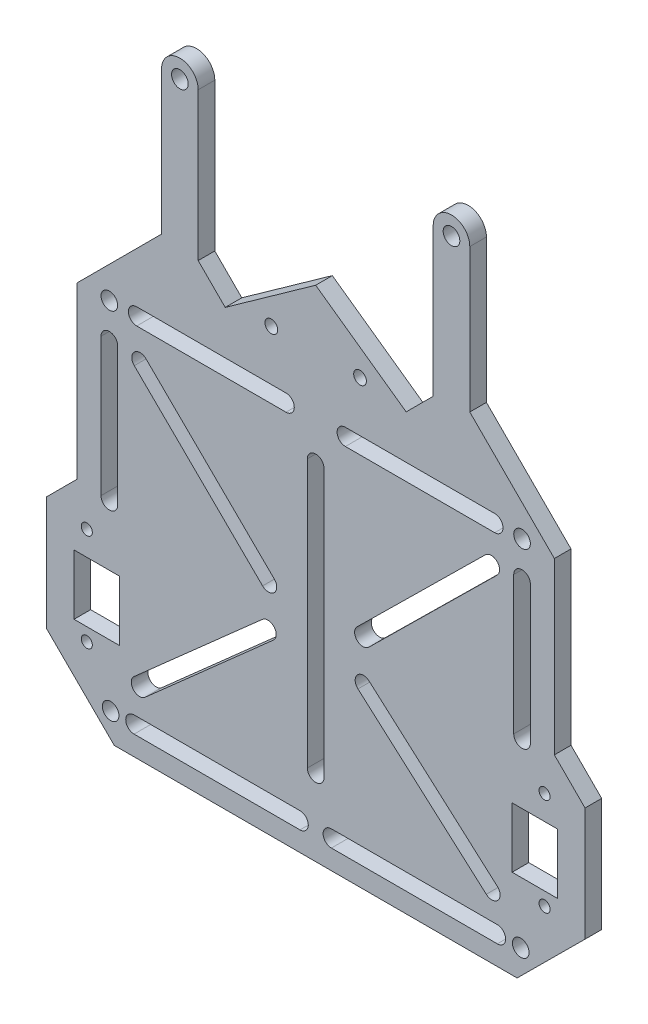
SolidWorks part; units mm, degrees
ref_plane "前视基准面" through (0, 0, 0) normal (0, 0, 1) x (1, 0, 0)
ref_plane "上视基准面" through (0, 0, 0) normal (0, 1, 0) x (1, 0, 0)
ref_plane "右视基准面" through (0, 0, 0) normal (1, 0, 0) x (0, 0, -1)
other "Configuration Table"
sketch "Model" plane through (0, 0, 0) normal (0, 0, 1) x (1, 0, 0)
  line L0 (-43.0594, 38.2199) -> (-48.5923, 32.687)
  line L1 (-43.0594, 68.8966) -> (-43.0594, 38.2199)
  line L2 (-27.8, 84.1561) -> (-43.0594, 68.8966)
  line L5 (-36.3443, 0) -> (36.3443, 0)
  line L12 (48.5923, 32.687) -> (48.5923, 12.1825)
  line L13 (48.5923, 12.1825) -> (36.3443, 0)
  line L14 (-48.5923, 12.1825) -> (-36.3443, 0)
  line L15 (-48.5923, 32.687) -> (-48.5923, 12.1825)
  line L16 (0, 136.8559) -> (0, -25.8131) construction
  line L25 (27.8, 84.1561) -> (43.0594, 68.8966)
  line L26 (43.0594, 68.8966) -> (43.0594, 38.2199)
  line L27 (43.0594, 38.2199) -> (48.5923, 32.687)
  line L28 (35.4376, 26.9114) -> (35.4376, 16.0731)
  line L29 (-43.5995, 26.9114) -> (-35.4376, 26.9114)
  line L30 (-43.5995, 26.9114) -> (-43.5995, 16.0731)
  line L31 (-43.5995, 16.0731) -> (-35.4376, 16.0731)
  line L32 (-35.4376, 26.9114) -> (-35.4376, 16.0731)
  line L33 (43.5995, 16.0731) -> (35.4376, 16.0731)
  line L34 (43.5995, 26.9114) -> (35.4376, 26.9114)
  line L35 (43.5995, 26.9114) -> (43.5995, 16.0731)
  line L36 (-32.2945, 69.0504) -> (-5.3615, 69.0504) construction
  line L37 (-32.2945, 70.5504) -> (-5.3615, 70.5504)
  line L38 (-32.2945, 67.5504) -> (-5.3615, 67.5504)
  line L39 (-37.227, 62.7286) -> (-37.227, 37.8282) construction
  line L40 (-35.727, 62.7286) -> (-35.727, 37.8282)
  line L41 (-38.727, 62.7286) -> (-38.727, 37.8282)
  line L42 (-31.6757, 62.1951) -> (-8.5261, 39.3676) construction
  line L43 (-30.6225, 63.2631) -> (-7.4729, 40.4357)
  line L44 (-32.7289, 61.127) -> (-9.5793, 38.2996)
  line L45 (-8.6217, 31.9272) -> (-31.7714, 11.4226) construction
  line L46 (-7.6272, 30.8043) -> (-30.7768, 10.2998)
  line L47 (-9.6163, 33.05) -> (-32.7659, 12.5455)
  line L48 (-32.7659, 5.0508) -> (-2.8347, 5.0508) construction
  line L49 (-32.7659, 6.5508) -> (-2.8347, 6.5508)
  line L50 (-32.7659, 3.5508) -> (-2.8347, 3.5508)
  line L51 (32.7659, 5.0508) -> (2.8347, 5.0508) construction
  line L52 (32.7659, 6.5508) -> (2.8347, 6.5508)
  line L53 (32.7659, 3.5508) -> (2.8347, 3.5508)
  line L54 (8.6217, 31.9272) -> (31.7714, 11.4226) construction
  line L55 (7.6272, 30.8043) -> (30.7768, 10.2998)
  line L56 (9.6163, 33.05) -> (32.7659, 12.5455)
  line L57 (37.227, 62.7286) -> (37.227, 37.8282) construction
  line L58 (35.727, 62.7286) -> (35.727, 37.8282)
  line L59 (38.727, 62.7286) -> (38.727, 37.8282)
  line L60 (31.6757, 62.1951) -> (8.5261, 39.3676) construction
  line L61 (30.6225, 63.2631) -> (7.4729, 40.4357)
  line L62 (32.7289, 61.127) -> (9.5793, 38.2996)
  line L63 (32.2945, 69.0504) -> (5.3615, 69.0504) construction
  line L64 (32.2945, 70.5504) -> (5.3615, 70.5504)
  line L65 (32.2945, 67.5504) -> (5.3615, 67.5504)
  line L66 (0, 62.1951) -> (0, 13.8889) construction
  line L67 (1.5, 62.1951) -> (1.5, 13.8889)
  line L68 (-1.5, 62.1951) -> (-1.5, 13.8889)
  line L69 (-27.8, 84.1561) -> (-27.8, 110)
  line L70 (-21.2, 110) -> (-21.2, 83.3141)
  line L72 (27.8, 84.1561) -> (27.8, 110)
  line L74 (21.2, 110) -> (21.2, 83.3141)
  line L75 (-21.2, 83.3141) -> (-16.3245, 78.4386)
  line L76 (-16.3245, 78.4386) -> (0, 90.0637)
  line L77 (16.3245, 78.4386) -> (0, 90.0637)
  line L78 (21.2, 83.3141) -> (16.3245, 78.4386)
  circle A2 centre (-24.5, 110) radius 1.5
  circle A3 centre (8, 79.6327) radius 1.15
  circle A4 centre (36.9906, 5.0508) radius 1.5
  circle A5 centre (37.227, 69.0504) radius 1.5
  circle A6 centre (-41.2923, 13.694) radius 1
  circle A7 centre (-41.2923, 31.294) radius 1
  circle A8 centre (41.2923, 31.294) radius 1
  circle A9 centre (-37.227, 69.0504) radius 1.5
  circle A10 centre (-36.9906, 5.0508) radius 1.5
  circle A11 centre (41.2923, 13.694) radius 1
  circle A12 centre (-8, 79.6327) radius 1.15
  arc A14 (-21.2, 110) -> (-27.8, 110) centre (-24.5, 110) ccw
  arc A15 (-32.2945, 70.5504) -> (-32.2945, 67.5504) centre (-32.2945, 69.0504) ccw
  arc A16 (-5.3615, 67.5504) -> (-5.3615, 70.5504) centre (-5.3615, 69.0504) ccw
  arc A17 (-35.727, 62.7286) -> (-38.727, 62.7286) centre (-37.227, 62.7286) ccw
  arc A18 (-38.727, 37.8282) -> (-35.727, 37.8282) centre (-37.227, 37.8282) ccw
  arc A19 (-30.6225, 63.2631) -> (-32.7289, 61.127) centre (-31.6757, 62.1951) ccw
  arc A20 (-9.5793, 38.2996) -> (-7.4729, 40.4357) centre (-8.5261, 39.3676) ccw
  arc A21 (-7.6272, 30.8043) -> (-9.6163, 33.05) centre (-8.6217, 31.9272) ccw
  arc A22 (-32.7659, 12.5455) -> (-30.7768, 10.2998) centre (-31.7714, 11.4226) ccw
  arc A23 (-32.7659, 6.5508) -> (-32.7659, 3.5508) centre (-32.7659, 5.0508) ccw
  arc A24 (-2.8347, 3.5508) -> (-2.8347, 6.5508) centre (-2.8347, 5.0508) ccw
  arc A25 (32.7659, 6.5508) -> (32.7659, 3.5508) centre (32.7659, 5.0508) cw
  arc A26 (2.8347, 3.5508) -> (2.8347, 6.5508) centre (2.8347, 5.0508) cw
  arc A27 (7.6272, 30.8043) -> (9.6163, 33.05) centre (8.6217, 31.9272) cw
  arc A28 (32.7659, 12.5455) -> (30.7768, 10.2998) centre (31.7714, 11.4226) cw
  arc A29 (35.727, 62.7286) -> (38.727, 62.7286) centre (37.227, 62.7286) cw
  arc A30 (38.727, 37.8282) -> (35.727, 37.8282) centre (37.227, 37.8282) cw
  arc A31 (30.6225, 63.2631) -> (32.7289, 61.127) centre (31.6757, 62.1951) cw
  arc A32 (9.5793, 38.2996) -> (7.4729, 40.4357) centre (8.5261, 39.3676) cw
  arc A33 (32.2945, 70.5504) -> (32.2945, 67.5504) centre (32.2945, 69.0504) cw
  arc A34 (5.3615, 67.5504) -> (5.3615, 70.5504) centre (5.3615, 69.0504) cw
  arc A35 (1.5, 62.1951) -> (-1.5, 62.1951) centre (0, 62.1951) ccw
  arc A36 (-1.5, 13.8889) -> (1.5, 13.8889) centre (0, 13.8889) ccw
  arc A37 (21.2, 110) -> (27.8, 110) centre (24.5, 110) cw
  circle A38 centre (24.5, 110) radius 1.5
  point P17 (-21.2, 81.8739)
  point P40 (0, 88.2193)
  point P47 (-16.3245, 76.9768)
  point P50 (0, 0)
  point P52 (0, 90.0637)
  point P53 (-24.5, 108.5382)
  point P56 (0, 0)
  point P67 (-18.828, 69.0504)
  point P72 (-37.227, 50.2784)
  point P79 (-20.1009, 50.7814)
  point P88 (-20.1965, 21.6749)
  point P95 (-17.8003, 5.0508)
  point P102 (17.8003, 5.0508)
  point P109 (20.1965, 21.6749)
  point P116 (37.227, 50.2784)
  point P123 (20.1009, 50.7814)
  point P130 (18.828, 69.0504)
  point P137 (0, 38.042)
  dimension "D11" = 2
  dimension "D12" = 3
  dimension "D15" = 3
  dimension "D20" = 3
  dimension "D6" = 3.3
  dimension "D8" = 110
  dimension "D1" = 17.6
  dimension "D2" = 7.3
  dimension "D3" = 8
  dimension "D4" = 36.9906
  dimension "D5" = 64
  dimension "D7" = 24.5
  dimension "D10" = 30.6767
  dimension "D16" = 135
  dimension "D17" = 135
  dimension "D19" = 3
  dimension "D21" = 3
  dimension "D22" = 3
  dimension "D23" = 3
  dimension "D24" = 3
  dimension "D25" = 3
extrude "凸台-拉伸1" add sketch "Model" along normal blind 3
